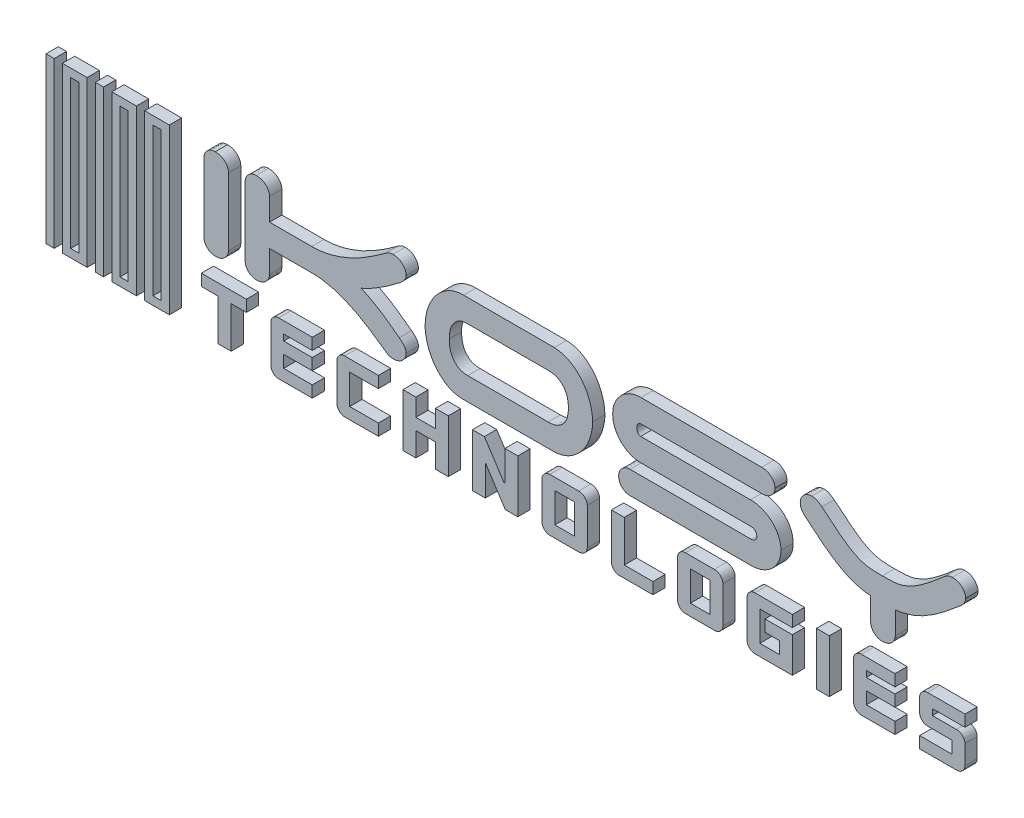
SolidWorks part; units mm, degrees
other "Symbol Extrude 1-1"
other "Symbol Extrude 2-0"
other "Symbol Extrude 3-1"
other "Text Extrude I"
other "Text Extrude K"
other "Text Extrude O"
other "Text Extrude S"
other "Text Extrude Y" parameters "D1"=6.2983, "D2"=2.0167, "D3"=11.6967, "D4"=11.6967, "D5"=1.4517, "D6"=1.4517, "D7"=14.1973, "D8"=14.1973, "D9"=30.15, "D10"=33.5, "D11"=33.5, "D12"=33.5, "D13"=30.15
ref_plane "Front Plane" through (0, 0, 0) normal (0, 0, 1) x (1, 0, 0)
ref_plane "Top Plane" through (0, 0, 0) normal (0, 1, 0) x (1, 0, 0)
ref_plane "Right Plane" through (0, 0, 0) normal (1, 0, 0) x (0, 0, -1)
sketch "Insertion Point Sketch" plane through (0, 0, 0) normal (0, 0, 1) x (1, 0, 0)
  line L0 (-3.25, -3.25) -> (-3.25, 0) construction
  line L1 (-3.25, -3.25) -> (0, -3.25) construction
  point P2 (0, 0)
  point P5 (0, 0)
  dimension "D1" = 3.25
  dimension "D2" = 3.25
sketch "Symbol Sketch" plane through (0, 0, 0) normal (0, 0, 1) x (1, 0, 0)
  line L1 (0, 33.5) -> (1.675, 33.5)
  line L2 (0, 33.5) -> (0, 0)
  line L3 (0, 0) -> (1.675, 0)
  line L4 (1.675, 33.5) -> (1.675, 0)
  line L5 (5.025, 31.825) -> (6.7, 31.825)
  line L6 (5.025, 31.825) -> (5.025, 1.675)
  line L7 (5.025, 1.675) -> (6.7, 1.675)
  line L8 (6.7, 31.825) -> (6.7, 1.675)
  line L9 (3.35, 33.5) -> (8.375, 33.5)
  line L10 (3.35, 33.5) -> (3.35, 0)
  line L11 (3.35, 0) -> (8.375, 0)
  line L12 (8.375, 33.5) -> (8.375, 0)
  line L13 (10.05, 33.5) -> (11.725, 33.5)
  line L14 (10.05, 33.5) -> (10.05, 0)
  line L15 (10.05, 0) -> (11.725, 0)
  line L16 (11.725, 33.5) -> (11.725, 0)
  line L17 (13.4, 33.5) -> (18.425, 33.5)
  line L18 (13.4, 33.5) -> (13.4, 0)
  line L19 (13.4, 0) -> (18.425, 0)
  line L20 (18.425, 33.5) -> (18.425, 0)
  line L21 (15.075, 31.825) -> (16.75, 31.825)
  line L22 (15.075, 31.825) -> (15.075, 1.675)
  line L23 (15.075, 1.675) -> (16.75, 1.675)
  line L24 (16.75, 31.825) -> (16.75, 1.675)
  line L25 (20.1, 33.5) -> (25.125, 33.5)
  line L26 (20.1, 33.5) -> (20.1, 0)
  line L27 (20.1, 0) -> (25.125, 0)
  line L28 (25.125, 33.5) -> (25.125, 0)
  line L29 (21.775, 31.825) -> (23.45, 31.825)
  line L30 (21.775, 31.825) -> (21.775, 1.675)
  line L31 (21.775, 1.675) -> (23.45, 1.675)
  line L32 (23.45, 31.825) -> (23.45, 1.675)
  dimension "D1" = 1.675
  dimension "D2" = 1.675
  dimension "D3" = 1.675
  dimension "D4" = 1.675
  dimension "D5" = 1.675
  dimension "D6" = 1.675
  dimension "D7" = 1.675
  dimension "D8" = 33.5
  dimension "D9" = 1.675
  dimension "D10" = 1.675
  dimension "D11" = 1.675
  dimension "D12" = 1.675
  dimension "D13" = 1.675
extrude "Symbol Extrude" add sketch "Symbol Sketch" along normal blind 2.5
sketch "Text Sketch" plane through (0, 0, 0) normal (0, 0, 1) x (1, 0, 0)
  line L0 (25.125, 33.5) -> (187.5, 33.5) construction
  line L1 (187.5, 33.5) -> (187.5, 0) construction
  text T0 "ikosy" font "Space Age" height 18.425
  text T1 "TECHNOLOGIES" font "Alien Encounters Solid" height 10.75
  dimension "D1" = 30.125
  dimension "D2" = 12.075
  dimension "D3" = 1.1
  dimension "D4" = 187.5
extrude "Text Extrude" add sketch "Text Sketch" along normal blind 2.5 separate body
equation "\"Logo Height\"= \"Total Height\" - 2 * \"Border\""
equation "\"Total Height\"= 40mm"
equation "\"Border\"= 3.25mm"
equation "\"Symbol Width\"= \"Logo Height\" * 0.75"
equation "\"Line Width\"= \"Symbol Width\" / 15"
equation "\"D2@Symbol Sketch\" = \"Line Width\""
equation "\"D1@Symbol Sketch\" = \"Line Width\""
equation "\"D3@Symbol Sketch\" = \"Line Width\""
equation "\"D4@Symbol Sketch\" = \"Line Width\""
equation "\"D5@Symbol Sketch\" = \"Line Width\""
equation "\"D6@Symbol Sketch\" = \"Line Width\""
equation "\"D7@Symbol Sketch\" = \"Line Width\""
equation "\"D8@Symbol Sketch\" = \"Logo Height\""
equation "\"D9@Symbol Sketch\" = \"Line Width\""
equation "\"D10@Symbol Sketch\" = \"Line Width\""
equation "\"D11@Symbol Sketch\" = \"Line Width\""
equation "\"D12@Symbol Sketch\" = \"Line Width\""
equation "\"D13@Symbol Sketch\" = \"Line Width\""
equation "\"Ikosy X Position\"= \"Symbol Width\" + 5mm"
equation "\"Ikosy Y Position\"= ( 1 - 0.55 ) * \"Logo Height\" - 3"
equation "\"D2@Text Sketch\" = \"Ikosy Y Position\""
equation "\"D1@Text Sketch\" = \"Ikosy X Position\""
equation "\"D1@Insertion Point Sketch\" = \"Border\""
equation "\"D2@Insertion Point Sketch\" = \"Border\""
